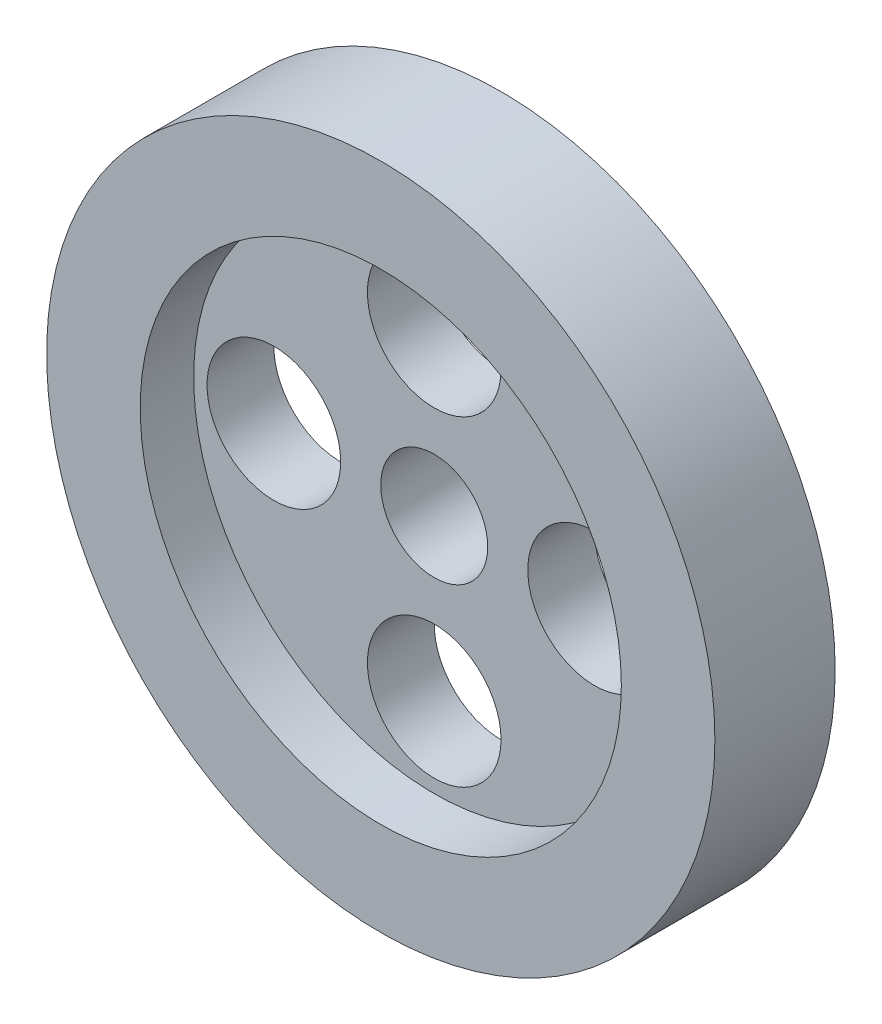
SolidWorks part; units mm, degrees
ref_plane "Front Plane" through (0, 0, 0) normal (0, 0, 1) x (1, 0, 0)
ref_plane "Top Plane" through (0, 0, 0) normal (0, 1, 0) x (1, 0, 0)
ref_plane "Right Plane" through (0, 0, 0) normal (1, 0, 0) x (0, 0, -1)
sketch "Sketch1" plane through (0, 0, 0) normal (0, 0, 1) x (1, 0, 0)
  circle A0 centre (0, 0) radius 25
  circle A1 centre (0, 0) radius 12 construction
  circle A2 centre (0, 12) radius 5
  circle A3 centre (12, 0) radius 5
  circle A4 centre (0, -12) radius 5
  circle A5 centre (-12, 0) radius 5
  circle A6 centre (0, 0) radius 4
  point P15 (0, 0)
  dimension "D1" = 50
  dimension "D2" = 10
  dimension "D3" = 4
  dimension "D4" = 8
  dimension "D5" = 24
extrude "Boss-Extrude1" add sketch "Sketch1" along normal blind 9
sketch "Sketch2" plane through (0, 0, 9) normal (0, 0, 1) x (1, 0, 0)
  circle A0 centre (0, 0) radius 18
  dimension "D1" = 36
extrude "Cut-Extrude1" cut sketch "Sketch2" against normal blind 4
sketch "Sketch3" plane through (0, 0, 0) normal (0, 0, -1) x (-1, 0, 0)
  circle A0 centre (0, 0) radius 6
  circle A2 centre (0, 0) radius 4 construction
  circle A3 centre (0, 0) radius 4
  dimension "D1" = 12
extrude "Boss-Extrude5" add sketch "Sketch3" along normal blind 1
